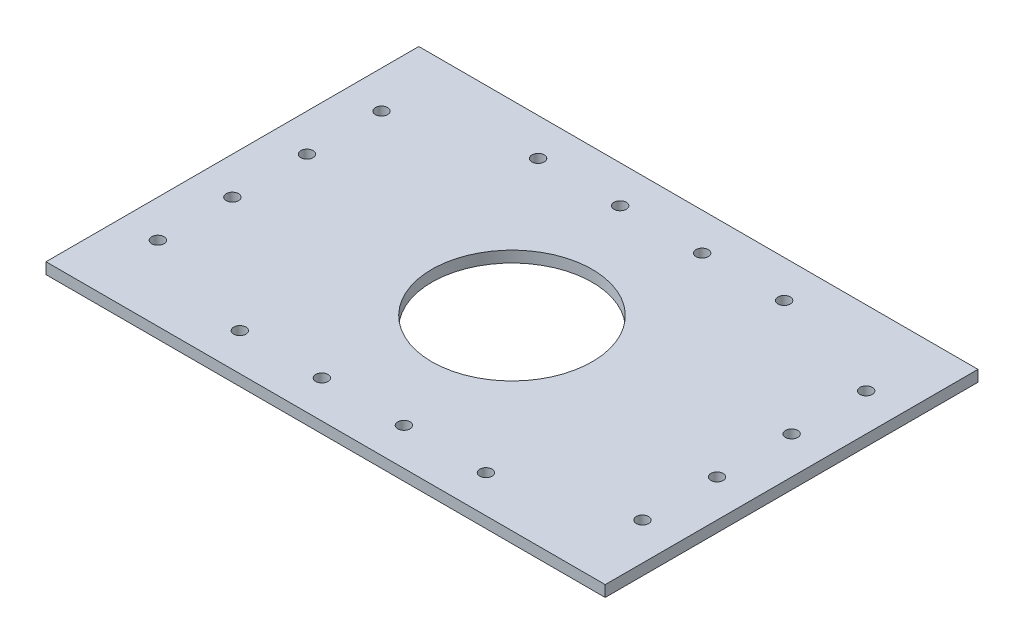
SolidWorks part; units mm, degrees
ref_plane "前视基准面" through (0, 0, 0) normal (0, 0, 1) x (1, 0, 0)
ref_plane "上视基准面" through (0, 0, 0) normal (0, 1, 0) x (1, 0, 0)
ref_plane "右视基准面" through (0, 0, 0) normal (1, 0, 0) x (0, 0, -1)
other "Configuration Table"
sketch "草图1" plane through (0, 0, 0) normal (0, 1, 0) x (1, 0, 0)
  line L0 (0, 0) -> (0, 77.0107) construction
  line L1 (-75, 50) -> (75, 50)
  line L2 (-75, 50) -> (-75, -50)
  line L3 (-75, -50) -> (75, -50)
  line L4 (75, 50) -> (75, -50)
  line L5 (-55, 0) -> (55, 0) construction
  line L6 (-75, -50) -> (75, 50) construction
  circle A0 centre (0, 0) radius 21.5
  circle A1 centre (-65, 30) radius 1.65
  circle A2 centre (-65, 10) radius 1.65
  circle A3 centre (-65, -10) radius 1.65
  circle A4 centre (-65, -30) radius 1.65
  circle A5 centre (65, -30) radius 1.65
  circle A6 centre (65, -10) radius 1.65
  circle A7 centre (65, 10) radius 1.65
  circle A8 centre (65, 30) radius 1.65
  circle A9 centre (33, 40) radius 1.65
  circle A13 centre (11, 40) radius 1.65
  circle A14 centre (-11, 40) radius 1.65
  circle A15 centre (-33, 40) radius 1.65
  circle A16 centre (33, -40) radius 1.65
  circle A17 centre (11, -40) radius 1.65
  circle A18 centre (-11, -40) radius 1.65
  circle A19 centre (-33, -40) radius 1.65
  point P0 (0, 0)
  dimension "D1" = 43
  dimension "D5" = 20
  dimension "D7" = 3.3
  dimension "D9" = 3.3
  dimension "D11" = 4
  dimension "D2" = 100
  dimension "D3" = 150
  dimension "D4" = 10
  dimension "D8" = 42
  dimension "D10" = 10
  dimension "D6" = 4
extrude "凸台-拉伸1" add sketch "草图1" along normal blind 3
